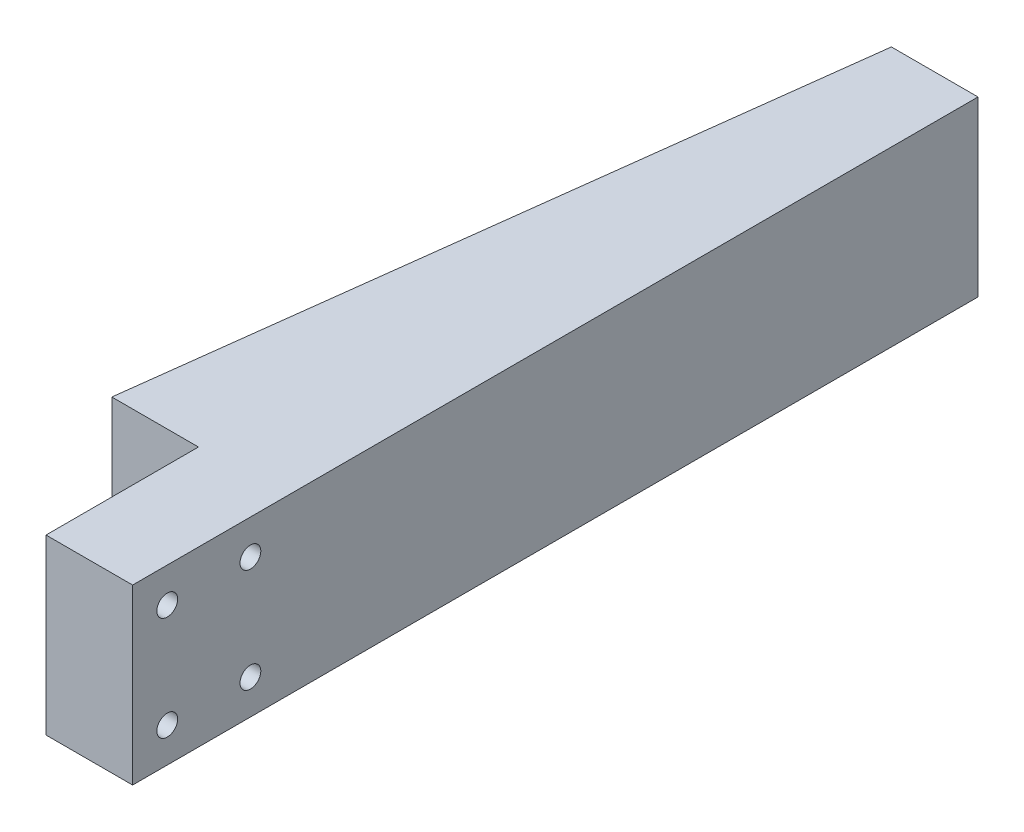
SolidWorks part; units mm, degrees
ref_plane "Front Plane" through (0, 0, 0) normal (0, 0, 1) x (1, 0, 0)
ref_plane "Top Plane" through (0, 0, 0) normal (0, 1, 0) x (1, 0, 0)
ref_plane "Right Plane" through (0, 0, 0) normal (1, 0, 0) x (0, 0, -1)
sketch "Sketch1" plane through (0, 0, 0) normal (1, 0, 0) x (0, 0, -1)
  line L1 (0, 0) -> (122, 0)
  line L2 (0, 0) -> (0, 25)
  line L3 (0, 25) -> (122, 25)
  line L4 (122, 0) -> (122, 25)
  circle A0 centre (5, 20) radius 1.5
  circle A1 centre (17, 20) radius 1.5
  circle A2 centre (17, 5) radius 1.5
  circle A3 centre (5, 5) radius 1.5
  dimension "D5" = 3
  dimension "D8" = 3
  dimension "D13" = 3
  dimension "D14" = 3
  dimension "D1" = 122
  dimension "D2" = 25
  dimension "D3" = 5
  dimension "D4" = 5
  dimension "D6" = 17
  dimension "D7" = 5
  dimension "D9" = 17
  dimension "D10" = 5
  dimension "D11" = 15
  dimension "D12" = 15
extrude "Boss-Extrude1" add sketch "Sketch1" against normal blind 12.5
sketch "Sketch2" plane through (0, 25, 0) normal (0, 1, 0) x (1, 0, 0)
  line L0 (-12.5, 122) -> (-25, 22)
  line L1 (-25, 22) -> (-12.5, 22)
  line L2 (-12.5, 122) -> (-12.5, 0) construction
  line L3 (-12.5, 122) -> (-12.5, 22)
  line L4 (-12.5, 0) -> (0, 0) construction
  dimension "D1" = 22
  dimension "D2" = 12.5
extrude "Boss-Extrude2" add sketch "Sketch2" against normal blind 25
